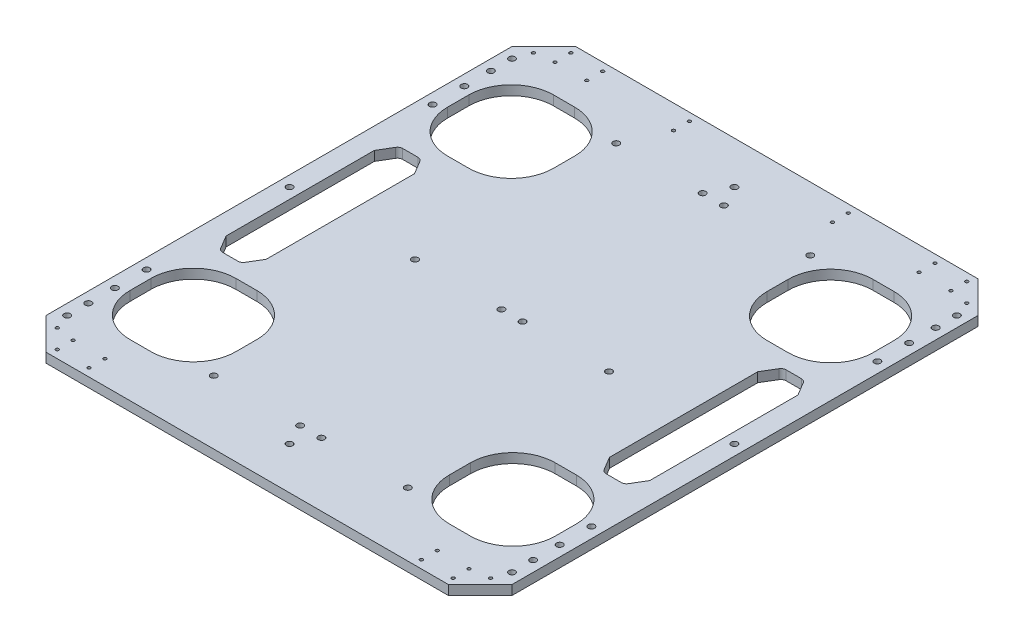
SolidWorks part; units mm, degrees
ref_plane "Alzado" through (0, 0, 0) normal (0, 0, 1) x (1, 0, 0)
ref_plane "Planta" through (0, 0, 0) normal (0, 1, 0) x (1, 0, 0)
ref_plane "Vista lateral" through (0, 0, 0) normal (1, 0, 0) x (0, 0, -1)
sketch "Croquis1" plane through (0, 0, 0) normal (0, 1, 0) x (1, 0, 0)
  line L1 (-220, 220) -> (220, 220)
  line L2 (-220, 220) -> (-220, -220)
  line L3 (-220, -220) -> (220, -220)
  line L4 (220, 220) -> (220, -220)
  line L5 (-220, 220) -> (220, -220) construction
  line L6 (-220, -220) -> (220, 220) construction
  point P0 (0, 0)
  dimension "D1" = 440
extrude "Saliente-Extruir1" add sketch "Croquis1" along normal blind 9
sketch "Croquis2" plane through (0, 9, 0) normal (0, 1, 0) x (1, 0, 0)
  line L0 (-220, 0) -> (0, 0) construction
  line L1 (-220, 220) -> (-220, -220) construction
  line L2 (0, 0) -> (0, 220) construction
  line L3 (220, 220) -> (-220, 220) construction
  line L4 (-220, 210) -> (220, 210) construction
  line L5 (220, -220) -> (220, 220) construction
  line L6 (-210, 220) -> (-210, -220) construction
  line L7 (-220, -220) -> (220, -220) construction
  line L8 (-10, 220) -> (-10, -220) construction
  line L9 (-220, 200) -> (220, 200) construction
  line L10 (-101.6, 220) -> (-101.6, -220) construction
  line L11 (-91.6, 200) -> (-91.6, 0) construction
  circle A0 centre (-210, 210) radius 2
  circle A2 centre (0, 210) radius 2
  circle A3 centre (-210, 190) radius 2
  circle A4 centre (-10, 190) radius 2
  circle A5 centre (-210, 0) radius 2
  circle A6 centre (-10, 0) radius 2
  circle A7 centre (0, -210) radius 2
  circle A8 centre (-10, -190) radius 2
  circle A9 centre (-210, -190) radius 2
  circle A10 centre (-210, -210) radius 2
  circle A11 centre (10, -190) radius 2
  circle A12 centre (210, -210) radius 2
  circle A13 centre (210, -190) radius 2
  circle A14 centre (210, 0) radius 2
  circle A15 centre (10, 0) radius 2
  circle A16 centre (10, 190) radius 2
  circle A17 centre (210, 190) radius 2
  circle A18 centre (210, 210) radius 2
  circle A19 centre (-91.6, 190) radius 2
  circle A20 centre (91.6, 190) radius 2
  circle A21 centre (-91.6, 0) radius 2
  circle A23 centre (91.6, -190) radius 2
  circle A24 centre (-91.6, -190) radius 2
  circle A25 centre (91.6, 0) radius 2
  dimension "D5" = 4
  dimension "D1" = 10
  dimension "D2" = 10
  dimension "D3" = 10
  dimension "D4" = 20
  dimension "D6" = 10
  dimension "D7" = 10
  dimension "D8" = 101.6
  dimension "D9" = 10
  dimension "D10" = 10
extrude "Cortar-Extruir1" cut sketch "Croquis2" against normal through all
sketch "Croquis3" plane through (0, 9, 0) normal (0, 1, 0) x (1, 0, 0)
  line L0 (-220, 0) -> (0, 0) construction
  line L1 (-220, 220) -> (-220, -220) construction
  line L2 (0, 0) -> (0, 220) construction
  line L3 (220, 220) -> (-220, 220) construction
  line L4 (-200, 220) -> (-200, -220) construction
  line L5 (-220, -220) -> (220, -220) construction
  line L6 (-200, -70) -> (-200, 70)
  line L7 (-200, 70) -> (-191, 85)
  line L8 (-191, 85) -> (-171, 85)
  line L9 (-171, 85) -> (-162, 70)
  line L10 (-162, 70) -> (-162, -70)
  line L11 (-171, -85) -> (-162, -70)
  line L12 (-200, -70) -> (-191, -85)
  line L13 (-191, -85) -> (-171, -85)
  line L14 (171, 85) -> (162, 70)
  line L15 (191, 85) -> (171, 85)
  line L16 (200, 70) -> (191, 85)
  line L17 (200, -70) -> (200, 70)
  line L18 (200, -70) -> (191, -85)
  line L19 (191, -85) -> (171, -85)
  line L20 (171, -85) -> (162, -70)
  line L21 (162, 70) -> (162, -70)
  line L22 (-181, -85) -> (-181, 85) construction
  point P20 (-162, 0)
  point P22 (-200, 0)
  dimension "D1" = 20
  dimension "D2" = 20
  dimension "D3" = 181
  dimension "D4" = 70
  dimension "D5" = 85
  dimension "D6" = 38
extrude "Cortar-Extruir2" cut sketch "Croquis3" against normal through all
sketch "Croquis4" plane through (0, 9, 0) normal (0, 1, 0) x (1, 0, 0)
  line L0 (-220, 0) -> (0, 0) construction
  line L1 (-220, 220) -> (-220, -220) construction
  line L2 (0, 0) -> (0, 220) construction
  line L3 (220, 220) -> (-220, 220) construction
  line L4 (-220, 200) -> (0, 200) construction
  line L5 (-200, 220) -> (-200, 0) construction
  line L6 (-220, 150) -> (-150.8, 150) construction
  line L7 (-150.8, 150) -> (-150.8, 220) construction
  line L8 (160.8, 100) -> (140.8, 100)
  line L9 (-160.8, 200) -> (-140.8, 200)
  line L10 (-200.8, 160) -> (-200.8, 140)
  line L11 (-160.8, 100) -> (-140.8, 100)
  line L12 (-100.8, 160) -> (-100.8, 140)
  line L13 (-200.8, 200) -> (-100.8, 100) construction
  line L14 (-200.8, 100) -> (-100.8, 200) construction
  line L15 (100.8, 160) -> (100.8, 140)
  line L16 (160.8, 200) -> (140.8, 200)
  line L17 (200.8, 160) -> (200.8, 140)
  line L18 (-160.8, -100) -> (-140.8, -100)
  line L19 (-100.8, -160) -> (-100.8, -140)
  line L20 (-160.8, -200) -> (-140.8, -200)
  line L21 (-200.8, -160) -> (-200.8, -140)
  line L22 (200.8, -160) -> (200.8, -140)
  line L23 (160.8, -200) -> (140.8, -200)
  line L24 (100.8, -160) -> (100.8, -140)
  line L25 (160.8, -100) -> (140.8, -100)
  arc A0 (-200.8, 140) -> (-160.8, 100) centre (-160.8, 140) ccw
  arc A1 (-140.8, 100) -> (-100.8, 140) centre (-140.8, 140) ccw
  arc A2 (-140.8, 200) -> (-100.8, 160) centre (-140.8, 160) cw
  arc A3 (-160.8, 200) -> (-200.8, 160) centre (-160.8, 160) ccw
  arc A4 (140.8, 100) -> (100.8, 140) centre (140.8, 140) cw
  arc A5 (140.8, 200) -> (100.8, 160) centre (140.8, 160) ccw
  arc A6 (200.8, 140) -> (160.8, 100) centre (160.8, 140) cw
  arc A7 (160.8, 200) -> (200.8, 160) centre (160.8, 160) cw
  arc A8 (-140.8, -100) -> (-100.8, -140) centre (-140.8, -140) cw
  arc A9 (-140.8, -200) -> (-100.8, -160) centre (-140.8, -160) ccw
  arc A10 (-200.8, -140) -> (-160.8, -100) centre (-160.8, -140) cw
  arc A11 (-160.8, -200) -> (-200.8, -160) centre (-160.8, -160) cw
  arc A12 (200.8, -140) -> (160.8, -100) centre (160.8, -140) ccw
  arc A13 (160.8, -200) -> (200.8, -160) centre (160.8, -160) ccw
  arc A14 (140.8, -200) -> (100.8, -160) centre (140.8, -160) cw
  arc A15 (140.8, -100) -> (100.8, -140) centre (140.8, -140) ccw
  dimension "D6" = 40
  dimension "D1" = 20
  dimension "D2" = 20
  dimension "D3" = 70
  dimension "D4" = 69.2
  dimension "D5" = 100
extrude "Cortar-Extruir3" cut sketch "Croquis4" against normal through all
fillet "Redondeo1" radius 5 8 edges at (171, 4.5, 85) (191, 4.5, 85) (171, 4.5, -85) (191, 4.5, -85) (-191, 4.5, 85) (-171, 4.5, 85) (-191, 4.5, -85) (-171, 4.5, -85)
sketch "Croquis5" plane through (0, 9, 0) normal (0, 1, 0) x (1, 0, 0)
  line L0 (-220, 0) -> (0, 0) construction
  line L1 (-220, 220) -> (-220, -220) construction
  line L2 (0, 0) -> (0, 220) construction
  line L3 (220, 220) -> (-220, 220) construction
  line L4 (-210, 220) -> (-210, 0) construction
  circle A0 centre (-210, 165) radius 2
  circle A1 centre (-210, 135) radius 2
  circle A2 centre (-210, -135) radius 2
  circle A3 centre (-210, -165) radius 2
  circle A4 centre (210, -165) radius 2
  circle A5 centre (210, -135) radius 2
  circle A6 centre (210, 135) radius 2
  circle A7 centre (210, 165) radius 2
  dimension "D1" = 4
  dimension "D2" = 55
  dimension "D3" = 30
extrude "Cortar-Extruir4" cut sketch "Croquis5" against normal through all
sketch "Croquis7" plane through (0, 9, 0) normal (0, 1, 0) x (1, 0, 0)
  line L0 (-220, 0) -> (0, 0) construction
  line L2 (0, 0) -> (0, 220) construction
  line L3 (220, 220) -> (-220, 220) construction
  line L4 (220, 220) -> (-220, 220)
  line L5 (-220, 220) -> (-190, 250)
  line L6 (-190, 250) -> (190, 250)
  line L7 (0, 250) -> (0, 220) construction
  line L8 (220, 220) -> (190, 250)
  line L9 (220, -220) -> (190, -250)
  line L10 (-190, -250) -> (190, -250)
  line L11 (-220, -220) -> (-190, -250)
  line L12 (220, -220) -> (-220, -220)
  line L13 (-220, 220) -> (-220, -220) construction
  line L14 (220, 220) -> (-220, 220) construction
  dimension "D1" = 30
  dimension "D2" = 135
extrude "Saliente-Extruir3" add sketch "Croquis7" against normal up to surface (9 mm away) up to face at (-210, 0, -133)
sketch "Croquis8" plane through (0, 9, 0) normal (0, 1, 0) x (1, 0, 0)
  line L0 (-220, 0) -> (0, 0) construction
  line L1 (-220, 220) -> (-220, -220) construction
  line L2 (0, 0) -> (0, 250) construction
  line L3 (190, 250) -> (-190, 250) construction
  line L4 (0, 235) -> (-205, 235) construction
  line L5 (-190, 250) -> (-220, 220) construction
  line L6 (-75, 235) -> (-75, 242.5) construction
  line L7 (-75, 242.5) -> (-186.8934, 242.5) construction
  line L8 (-194.8223, 234.5711) -> (-184.2157, 223.9645) construction
  line L9 (-199.6967, 229.6967) -> (-205, 235) construction
  line L10 (-184.6967, 244.6967) -> (-214.6967, 214.6967)
  line L11 (-184.6967, 244.6967) -> (-214.6967, 214.6967) construction
  line L12 (184.6967, 244.6967) -> (214.6967, 214.6967) construction
  line L13 (199.6967, 229.6967) -> (205, 235) construction
  line L14 (194.8223, 234.5711) -> (184.2157, 223.9645) construction
  line L15 (194.8223, -234.5711) -> (184.2157, -223.9645) construction
  line L16 (199.6967, -229.6967) -> (205, -235) construction
  line L17 (184.6967, -244.6967) -> (214.6967, -214.6967) construction
  line L18 (-184.6967, -244.6967) -> (-214.6967, -214.6967) construction
  line L19 (-199.6967, -229.6967) -> (-205, -235) construction
  line L20 (-194.8223, -234.5711) -> (-184.2157, -223.9645) construction
  circle A0 centre (-75, 242.5) radius 1.5
  circle A1 centre (-75, 227.5) radius 1.5
  circle A2 centre (75, 227.5) radius 1.5
  circle A3 centre (75, 242.5) radius 1.5
  circle A4 centre (-186.8934, 242.5) radius 1.5
  circle A5 centre (-204.5711, 224.8223) radius 1.5
  circle A6 centre (-194.8223, 234.5711) radius 1.5 construction
  circle A7 centre (-184.2157, 223.9645) radius 1.5 construction
  circle A8 centre (-193.9645, 214.2157) radius 1.5 construction
  circle A9 centre (-156.8934, 242.5) radius 1.5
  circle A10 centre (-156.8934, 227.5) radius 1.5
  circle A11 centre (-186.8934, 227.5) radius 1.5
  circle A12 centre (186.8934, 227.5) radius 1.5
  circle A13 centre (156.8934, 227.5) radius 1.5
  circle A14 centre (156.8934, 242.5) radius 1.5
  circle A15 centre (193.9645, 214.2157) radius 1.5 construction
  circle A16 centre (184.2157, 223.9645) radius 1.5 construction
  circle A17 centre (194.8223, 234.5711) radius 1.5 construction
  circle A18 centre (204.5711, 224.8223) radius 1.5
  circle A19 centre (186.8934, 242.5) radius 1.5
  circle A20 centre (186.8934, -242.5) radius 1.5
  circle A21 centre (204.5711, -224.8223) radius 1.5
  circle A22 centre (194.8223, -234.5711) radius 1.5 construction
  circle A23 centre (184.2157, -223.9645) radius 1.5 construction
  circle A24 centre (193.9645, -214.2157) radius 1.5 construction
  circle A25 centre (156.8934, -242.5) radius 1.5
  circle A26 centre (156.8934, -227.5) radius 1.5
  circle A27 centre (186.8934, -227.5) radius 1.5
  circle A28 centre (-186.8934, -227.5) radius 1.5
  circle A29 centre (-156.8934, -227.5) radius 1.5
  circle A30 centre (-156.8934, -242.5) radius 1.5
  circle A31 centre (-193.9645, -214.2157) radius 1.5 construction
  circle A32 centre (-184.2157, -223.9645) radius 1.5 construction
  circle A33 centre (-194.8223, -234.5711) radius 1.5 construction
  circle A34 centre (-204.5711, -224.8223) radius 1.5
  circle A35 centre (-186.8934, -242.5) radius 1.5
  dimension "D3" = 3
  dimension "D1" = 15
  dimension "D2" = 7.5
  dimension "D4" = 75
  dimension "D5" = 25
  dimension "D7" = 15
  dimension "D8" = 30
  dimension "D6" = 7.5
extrude "Cortar-Extruir7" cut sketch "Croquis8" against normal through all
sketch "Croquis9" plane through (0, 9, 0) normal (0, 1, 0) x (1, 0, 0)
  line L0 (-220, 0) -> (0, 0) construction
  line L1 (-220, 220) -> (-220, -220) construction
  line L2 (0, 0) -> (0, 250) construction
  line L3 (190, 250) -> (-190, 250) construction
  circle A0 centre (-210, 210) radius 3
  circle A1 centre (-210, 190) radius 3
  circle A2 centre (-210, 165) radius 3
  circle A3 centre (-210, 135) radius 3
  circle A4 centre (-210, 0) radius 3
  circle A5 centre (-91.6, 0) radius 3
  circle A6 centre (-10, 0) radius 3
  circle A7 centre (0, 210) radius 3
  circle A8 centre (-10, 190) radius 3
  circle A9 centre (-91.6, 190) radius 3
  circle A10 centre (210, 0) radius 3
  circle A11 centre (91.6, 0) radius 3
  circle A12 centre (10, 0) radius 3
  circle A13 centre (91.6, 190) radius 3
  circle A14 centre (10, 190) radius 3
  circle A15 centre (210, 135) radius 3
  circle A16 centre (210, 165) radius 3
  circle A17 centre (210, 190) radius 3
  circle A18 centre (210, 210) radius 3
  circle A19 centre (210, -210) radius 3
  circle A20 centre (210, -190) radius 3
  circle A21 centre (210, -165) radius 3
  circle A22 centre (210, -135) radius 3
  circle A23 centre (10, -190) radius 3
  circle A24 centre (91.6, -190) radius 3
  circle A25 centre (-91.6, -190) radius 3
  circle A26 centre (-10, -190) radius 3
  circle A27 centre (0, -210) radius 3
  circle A28 centre (-210, -135) radius 3
  circle A29 centre (-210, -165) radius 3
  circle A30 centre (-210, -190) radius 3
  circle A31 centre (-210, -210) radius 3
  dimension "D1" = 6
extrude "Cortar-Extruir8" cut sketch "Croquis9" against normal through all
